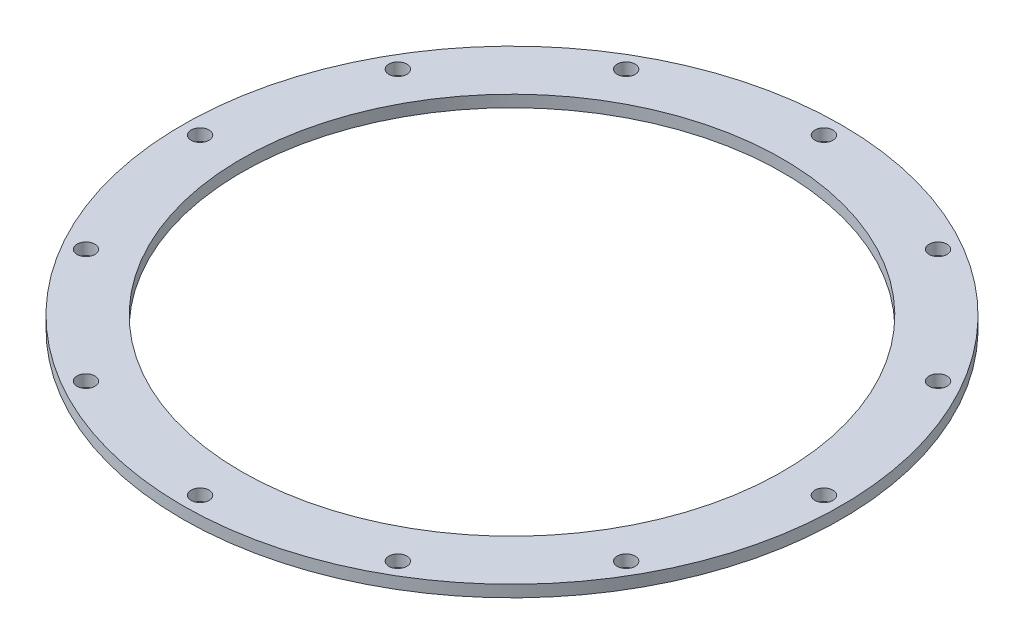
SolidWorks part; units mm, degrees
ref_plane "前视基准面" through (0, 0, 0) normal (0, 0, 1) x (1, 0, 0)
ref_plane "上视基准面" through (0, 0, 0) normal (0, 1, 0) x (1, 0, 0)
ref_plane "右视基准面" through (0, 0, 0) normal (1, 0, 0) x (0, 0, -1)
other "Configuration Table"
sketch "草图1" plane through (0, 0, 0) normal (0, 1, 0) x (1, 0, 0)
  line L0 (0, 56) -> (0, 46) construction
  line L1 (-56, 0) -> (-50, 0) construction
  line L2 (-50, 0) -> (-46, 0) construction
  circle A0 centre (0, 0) radius 56
  circle A1 centre (0, 0) radius 46
  circle A2 centre (-53, 0) radius 1.525
  circle A3 centre (0, 0) radius 50 construction
  circle A4 centre (-45.8993, 26.5) radius 1.525
  circle A5 centre (-26.5, 45.8993) radius 1.525
  circle A6 centre (0, 53) radius 1.525
  circle A7 centre (26.5, 45.8993) radius 1.525
  circle A8 centre (45.8993, 26.5) radius 1.525
  circle A9 centre (53, 0) radius 1.525
  circle A10 centre (45.8993, -26.5) radius 1.525
  circle A11 centre (26.5, -45.8993) radius 1.525
  circle A12 centre (0, -53) radius 1.525
  circle A13 centre (-26.5, -45.8993) radius 1.525
  circle A14 centre (-45.8993, -26.5) radius 1.525
  point P36 (0, 0)
  dimension "D1" = 4
  dimension "D2" = 100
  dimension "D4" = 3.05
  dimension "D3" = 6
  dimension "D5" = 12
extrude "凸台-拉伸1" add sketch "草图1" along normal blind 2
